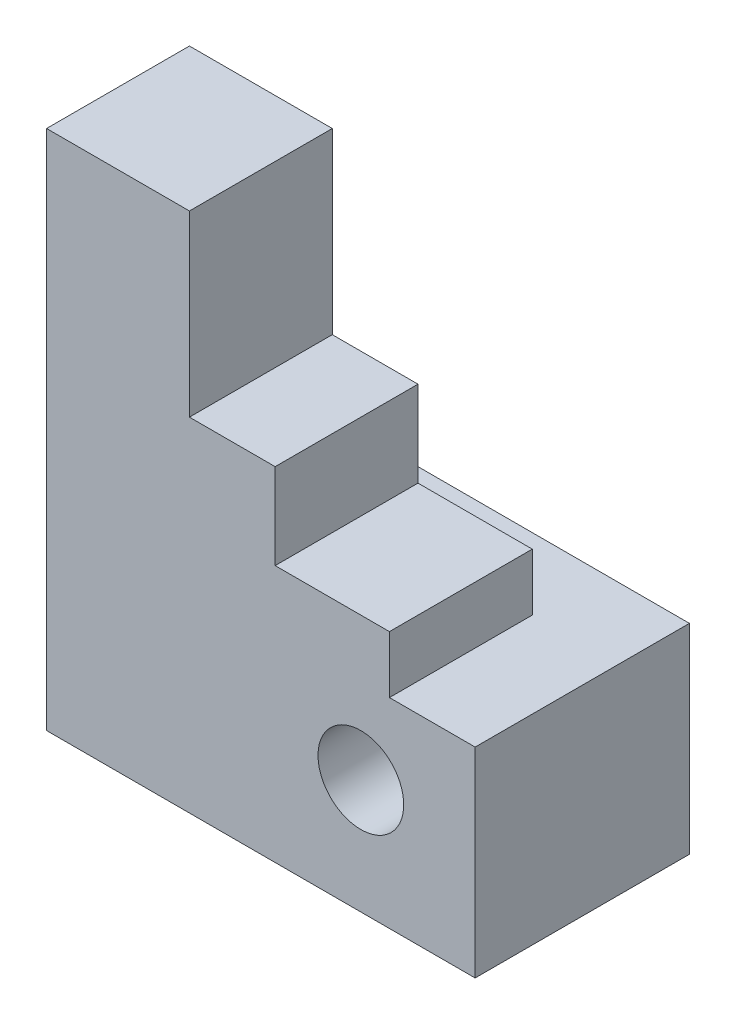
SolidWorks part; units mm, degrees
ref_plane "Front Plane" through (0, 0, 0) normal (0, 0, 1) x (1, 0, 0)
ref_plane "Top Plane" through (0, 0, 0) normal (0, 1, 0) x (1, 0, 0)
ref_plane "Right Plane" through (0, 0, 0) normal (1, 0, 0) x (0, 0, -1)
sketch "Sketch1" plane through (0, 0, 0) normal (0, 1, 0) x (1, 0, 0)
  point P0 (0, 0)
sketch "Sketch2" plane through (0, 0, 0) normal (0, 1, 0) x (1, 0, 0)
  line L0 (0, 0) -> (0, 30)
  line L1 (0, 30) -> (60, 30)
  line L2 (60, 30) -> (60, 0)
  line L3 (60, 0) -> (0, 0)
  dimension "D1" = 60
  dimension "D2" = 30
extrude "Boss-Extrude1" add sketch "Sketch2" along normal blind 28
sketch "Sketch3" plane through (0, 0, 0) normal (0, 0, 1) x (1, 0, 0)
  line L0 (44, 0) -> (44, 16) construction
  line L1 (0, 0) -> (60, 0) construction
  line L2 (44, 16) -> (60, 16) construction
  line L3 (60, 28) -> (60, 0) construction
  line L4 (0, 28) -> (0, 73)
  line L5 (0, 73) -> (20, 73)
  line L6 (20, 73) -> (20, 48)
  line L7 (20, 48) -> (32, 48)
  line L8 (32, 48) -> (32, 36)
  line L9 (32, 36) -> (48, 36)
  line L10 (48, 36) -> (48, 28)
  line L11 (0, 28) -> (60, 28) construction
  line L12 (48, 28) -> (0, 28)
  dimension "D1" = 16
  dimension "D3" = 45
  dimension "D4" = 8
  dimension "D5" = 12
  dimension "D6" = 12
  dimension "D7" = 12
  dimension "D8" = 20
extrude "Boss-Extrude3" add sketch "Sketch3" against normal blind 20 contours L5 L6 L7 L8 L9 L10 L12 L4
sketch "Sketch6" plane through (0, 0, -30) normal (0, 0, -1) x (-1, 0, 0)
  line L0 (-60, 16) -> (-44, 16) construction
  line L1 (-60, 28) -> (-60, 0) construction
  line L2 (-44, 16) -> (-44, 0) construction
  line L3 (-60, 0) -> (0, 0) construction
  circle A0 centre (-44, 16) radius 6
  dimension "D3" = 12
  dimension "D1" = 16
  dimension "D2" = 16
extrude "Cut-Extrude7" cut sketch "Sketch6" against normal blind 60 contours A0
